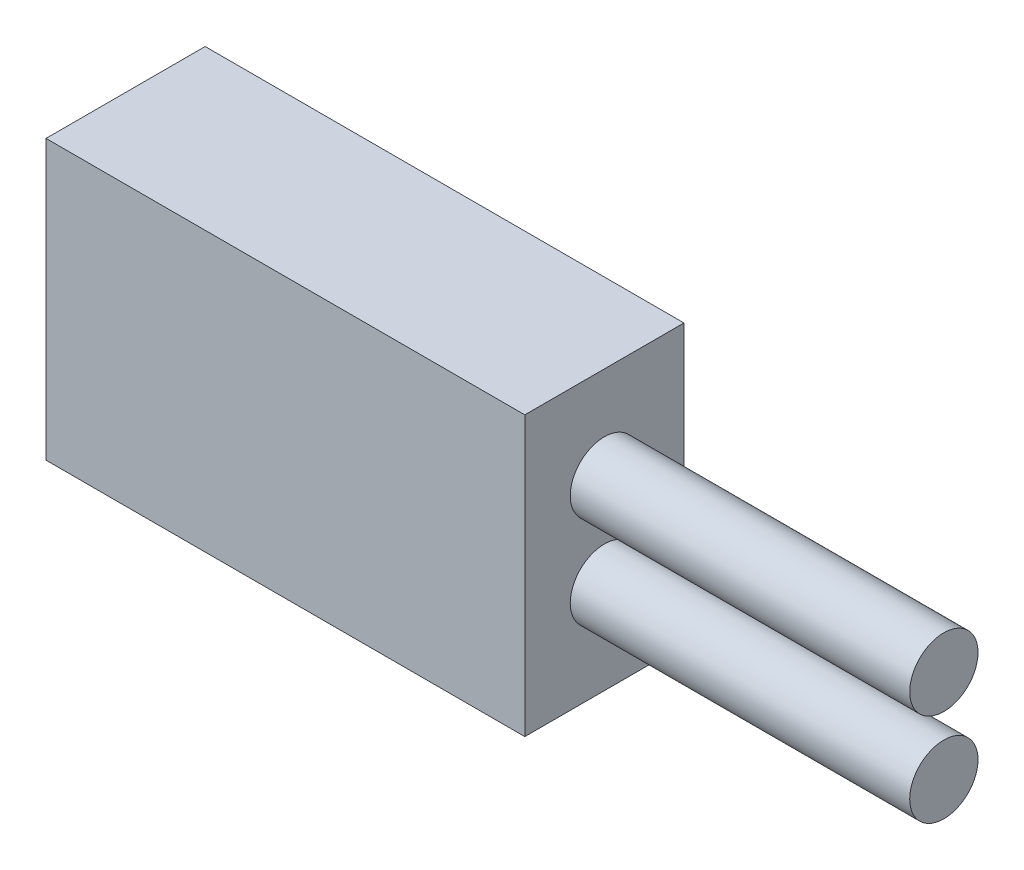
SolidWorks part; units mm, degrees
ref_plane "Front Plane" through (0, 0, 0) normal (0, 0, 1) x (1, 0, 0)
ref_plane "Top Plane" through (0, 0, 0) normal (0, 1, 0) x (1, 0, 0)
ref_plane "Right Plane" through (0, 0, 0) normal (1, 0, 0) x (0, 0, -1)
sketch "Sketch1" plane through (0, 0, 0) normal (0, 0, 1) x (1, 0, 0)
  line L1 (0, 0) -> (70.1, 0)
  line L2 (0, 0) -> (0, 40.8)
  line L3 (0, 40.8) -> (70.1, 40.8)
  line L4 (70.1, 0) -> (70.1, 40.8)
  dimension "D1" = 40.8
  dimension "D2" = 70.1
extrude "Boss-Extrude1" add sketch "Sketch1" along normal blind 23.3
sketch "Sketch2" plane through (70.1, 0, 0) normal (1, 0, 0) x (0, 0, -1)
  circle A0 centre (-11.65, 27.2) radius 5
  circle A1 centre (-11.65, 13.6) radius 5
extrude "Boss-Extrude2" add sketch "Sketch2" along normal blind 49.7
